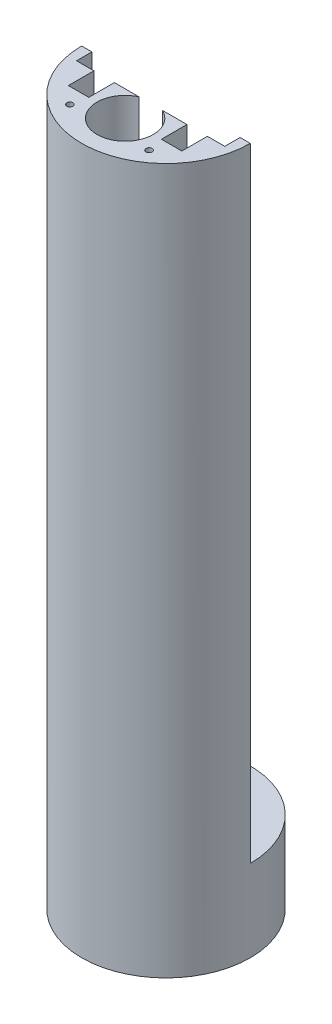
SolidWorks part; units mm, degrees
ref_plane "前视基准面" through (0, 0, 0) normal (0, 0, 1) x (1, 0, 0)
ref_plane "上视基准面" through (0, 0, 0) normal (0, 1, 0) x (1, 0, 0)
ref_plane "右视基准面" through (0, 0, 0) normal (1, 0, 0) x (0, 0, -1)
other "Configuration Table"
sketch "草图1" plane through (0, 0, 0) normal (0, 1, 0) x (1, 0, 0)
  circle A0 centre (0, 0) radius 16.5
  circle A1 centre (0, 0) radius 15.5
  dimension "D1" = 33
  dimension "D2" = 31
extrude "凸台-拉伸1" add sketch "草图1" along normal blind 6 contours A0
sketch "草图2" plane through (0, 6, 0) normal (0, 1, 0) x (1, 0, 0)
  line L0 (0, 0) -> (0, -8) construction
  line L1 (0, 5.1) -> (0, -1.9) construction
  line L2 (-6.1, -14.1) -> (6.1, -14.1)
  line L3 (-6.1, -14.1) -> (-6.1, -1.9)
  line L4 (-6.1, -1.9) -> (6.1, -1.9)
  line L5 (6.1, -14.1) -> (6.1, -1.9)
  line L6 (-6.1, -14.1) -> (6.1, -1.9) construction
  line L7 (-6.1, -1.9) -> (6.1, -14.1) construction
  line L8 (1.6, -1.9) -> (-1.6, -1.9)
  line L9 (1.6, -1.9) -> (1.6, 5.1)
  line L10 (1.6, 5.1) -> (-1.6, 5.1)
  line L11 (-1.6, -1.9) -> (-1.6, 5.1)
  circle A0 centre (0, -8) radius 4.25
  dimension "D1" = 8.5
  dimension "D2" = 8
  dimension "D3" = 12.2
  dimension "D4" = 3.2
  dimension "D5" = 7
extrude "切除-拉伸1" cut sketch "草图2" against normal through all contours A0
sketch "草图3" plane through (0, 0, 0) normal (0, -1, 0) x (1, 0, 0)
  circle A0 centre (-8.4853, 8.4853) radius 0.6
  circle A1 centre (8.4853, 8.4853) radius 0.6
  circle A2 centre (8.4853, -8.4853) radius 0.6
  circle A3 centre (-8.4853, -8.4853) radius 0.6
  dimension "D1" = 1.2
extrude "切除-拉伸2" cut sketch "草图3" against normal blind 3
sketch "草图4" plane through (0, 6, 0) normal (0, 1, 0) x (1, 0, 0)
  circle A0 centre (0, -8) radius 5.5
  circle A1 centre (0, -8) radius 4.25 construction
  circle M2 centre (0, 0) radius 16.5
  dimension "D1" = 11
extrude "凸台-拉伸2" add sketch "草图4" along normal blind 10 contours A0 M2
sketch "草图5" plane through (0, 16, 0) normal (0, 1, 0) x (1, 0, 0)
  line L0 (16.5, 0) -> (-16.5, 0)
  circle A0 centre (0, 0) radius 16.5 construction
  circle M2 centre (0, -8) radius 5.5
  circle M3 centre (0, 0) radius 16.5
extrude "凸台-拉伸3" add sketch "草图5" along normal blind 122 contours L0 M3 M2
sketch "草图6" plane through (0, 0, 0) normal (0, 0, -1) x (-1, 0, 0)
  line L0 (-16.5, 138) -> (16.5, 138) construction
  line L1 (-14.5, 138) -> (14.5, 138)
  line L2 (-14.5, 138) -> (-14.5, 98)
  line L3 (-14.5, 98) -> (14.5, 98)
  line L4 (14.5, 138) -> (14.5, 98)
  line L5 (0, 0) -> (0, 98) construction
  line L6 (-16.5, 0) -> (16.5, 0) construction
  line L7 (0, 78) -> (0, 98) construction
  line L8 (-5, 98) -> (5, 98)
  line L9 (-5, 98) -> (-5, 78)
  line L10 (-5, 78) -> (5, 78)
  line L11 (5, 98) -> (5, 78)
  dimension "D1" = 29
  dimension "D2" = 40
  dimension "D3" = 10
  dimension "D4" = 20
extrude "切除-拉伸3" cut sketch "草图6" against normal blind 3 contours L3 L4 L1 L2 | L11 L10 L9 L8
sketch "草图7" plane through (0, 0, 3) normal (0, 0, -1) x (-1, 0, 0)
  line L0 (5, 98) -> (14.5, 98) construction
  line L1 (7.1, 138) -> (11.1, 138)
  line L2 (7.1, 138) -> (7.1, 98)
  line L3 (7.1, 98) -> (11.1, 98)
  line L4 (11.1, 138) -> (11.1, 98)
  line L5 (-11.1, 138) -> (-7.1, 138)
  line L6 (-11.1, 138) -> (-11.1, 98)
  line L7 (-11.1, 98) -> (-7.1, 98)
  line L8 (-7.1, 138) -> (-7.1, 98)
  line L9 (-7.1, 138) -> (7.1, 138) construction
  line L10 (0, 138) -> (0, 0) construction
  line L11 (2.2913, 138) -> (14.5, 138) construction
  dimension "D1" = 4
  dimension "D2" = 14.2
extrude "切除-拉伸4" cut sketch "草图7" against normal blind 5
sketch "草图8" plane through (0, 0, 3) normal (0, 0, -1) x (-1, 0, 0)
  line L0 (-14.5, 133) -> (-11.1, 133) construction
  line L1 (-14.5, 138) -> (-14.5, 98) construction
  line L2 (-11.1, 138) -> (-11.1, 98) construction
  line L3 (-14.5, 138) -> (-11.1, 138) construction
  line L4 (11.1, 110) -> (14.5, 110) construction
  line L5 (11.1, 98) -> (11.1, 138) construction
  line L6 (14.5, 138) -> (14.5, 98) construction
  line L7 (5, 98) -> (14.5, 98) construction
  circle A0 centre (-12.8, 133) radius 0.4
  circle A1 centre (-12.8, 110) radius 0.4
  circle A2 centre (12.8, 133) radius 0.4
  circle A3 centre (12.8, 110) radius 0.4
  dimension "D2" = 0.8
  dimension "D1" = 5
  dimension "D3" = 12
extrude "切除-拉伸5" cut sketch "草图8" against normal blind 2
sketch "草图9" plane through (0, 0, 0) normal (0, 0, -1) x (-1, 0, 0)
  line L0 (0, 47) -> (0, 16) construction
  line L1 (0, 67) -> (0, 98) construction
  line L2 (-14.5, 98) -> (-5, 98) construction
  line L4 (16.5, 16) -> (-16.5, 16) construction
  circle A0 centre (0, 67) radius 0.6
  circle A1 centre (0, 47) radius 0.6
  dimension "D2" = 1.2
  dimension "D1" = 20
extrude "切除-拉伸6" cut sketch "草图9" against normal blind 2
sketch "草图10" plane through (0, 0, 0) normal (0, 0, -1) x (-1, 0, 0)
  circle A0 centre (-8.5, 87) radius 0.6
  circle A1 centre (8.5, 87) radius 0.6
  circle A2 centre (8.5, 27) radius 0.6
  circle A3 centre (-8.5, 27) radius 0.6
  dimension "D1" = 1.2
extrude "切除-拉伸7" cut sketch "草图10" against normal blind 3
sketch "草图11" plane through (0, 138, 0) normal (0, 1, 0) x (1, 0, 0)
  line L0 (7.7433, -11.0586) -> (0, 0) construction
  line L1 (5, 0) -> (-5, 0) construction
  line L2 (0, 0) -> (-7.7433, -11.0586) construction
  line L3 (0, 0) -> (0, -15.0826) construction
  circle A0 centre (7.7433, -11.0586) radius 0.6
  circle A1 centre (-7.7433, -11.0586) radius 0.6
  dimension "D3" = 1.2
  dimension "D1" = 35
  dimension "D2" = 35
  dimension "D4" = 13.5
extrude "切除-拉伸8" cut sketch "草图11" against normal blind 3
sketch "草图12" plane through (0, 0, 0) normal (0, -1, 0) x (-1, 0, 0)
  circle A0 centre (0, 0) radius 1.5
  dimension "D1" = 3
extrude "切除-拉伸9" cut sketch "草图12" against normal blind 40
